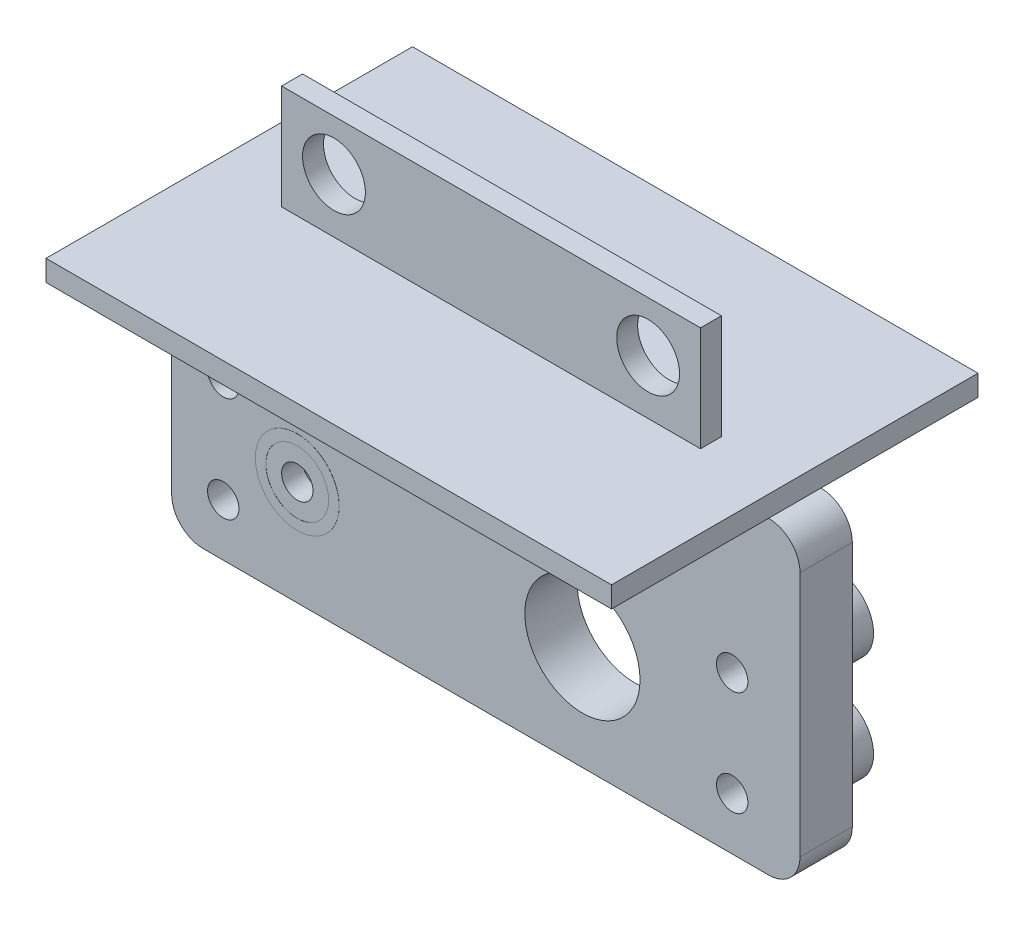
SolidWorks part; units mm, degrees
ref_plane "前视基准面" through (0, 0, 0) normal (0, 0, 1) x (1, 0, 0)
ref_plane "上视基准面" through (0, 0, 0) normal (0, 1, 0) x (1, 0, 0)
ref_plane "右视基准面" through (0, 0, 0) normal (1, 0, 0) x (0, 0, -1)
other "Configuration Table"
sketch "草图1" plane through (0, 0, 0) normal (0, 0, 1) x (1, 0, 0)
  line L0 (0, 0) -> (1.5, 0) construction
  line L2 (-15.5, 19.5) -> (38.5, 19.5)
  line L3 (-18.5, 16.5) -> (-18.5, -7)
  line L4 (-15.5, -10) -> (-9.175, -10)
  line L5 (41.5, 16.5) -> (41.5, -7)
  line L29 (33.3, -10) -> (38.5, -10)
  line L30 (11.5, 18.5) -> (11.5, 10.6886) construction
  line L33 (26.375, 18.5) -> (2.3684, 18.5) construction
  line L34 (33.3, -10) -> (30.825, -10)
  line L35 (-9.175, -10) -> (30.825, -10)
  circle A16 centre (-13.575, 5) radius 1.5
  circle A17 centre (-13.575, -5) radius 1.5
  circle A18 centre (35.025, 5) radius 1.5
  circle A19 centre (35.025, -5) radius 1.5
  arc A20 (38.5, 19.5) -> (41.5, 16.5) centre (38.5, 16.5) cw
  arc A21 (38.5, -10) -> (41.5, -7) centre (38.5, -7) ccw
  arc A22 (-18.5, -7) -> (-15.5, -10) centre (-15.5, -7) ccw
  arc A23 (-15.5, 19.5) -> (-18.5, 16.5) centre (-15.5, 16.5) ccw
  circle A32 centre (20.725, 0) radius 5.5
  dimension "D2" = 3
  dimension "D3" = 3
  dimension "D4" = 60
  dimension "D6" = 3
  dimension "D8" = 14.3
  dimension "D9" = 14.3
  dimension "D10" = 11
  dimension "D11" = 14.875
  dimension "D5" = 3
  dimension "D13" = 3
  dimension "D15" = 10
  dimension "D17" = 34.3
  dimension "D7" = 29.5
  dimension "D16" = 34.3
  dimension "D20" = 10
extrude "凸台-拉伸1" add sketch "草图1" along normal blind 5
sketch "草图3" plane through (0, 0, 5) normal (0, 0, 1) x (1, 0, 0)
  line L0 (-18.5, 16.5) -> (-18.5, -7) construction
  circle A1 centre (-6.5, 0) radius 3
  dimension "D1" = 12
extrude "拉伸-薄壁1" add sketch "草图3" along normal blind 0.01 thin
sketch "草图7" plane through (0, 19.5, 0) normal (0, 1, 0) x (1, 0, 0)
  line L0 (-15.5, -20) -> (-15.5, 15)
  line L1 (-15.5, -5) -> (-15.5, 0) construction
  line L2 (38.5, -20) -> (38.5, 15)
  line L3 (38.5, -5) -> (38.5, 0) construction
  line L4 (38.5, 15) -> (-15.5, 15)
  line L5 (-15.5, -2.5) -> (38.5, -2.5) construction
  line L6 (38.5, -20) -> (-15.5, -20)
  dimension "D1" = 35
extrude "凸台-拉伸2" add sketch "草图7" along normal blind 2
sketch "草图8" plane through (0, 0, 0) normal (0, 0, -1) x (-1, 0, 0)
  circle A0 centre (-35.025, 5) radius 1.5 construction
  circle A1 centre (-35.025, 5) radius 1.5
  circle A2 centre (-35.025, -5) radius 1.5 construction
  circle A3 centre (-35.025, -5) radius 1.5
  circle A4 centre (13.575, 5) radius 1.5 construction
  circle A5 centre (13.575, 5) radius 1.5
  circle A6 centre (13.575, -5) radius 1.5 construction
  circle A7 centre (13.575, -5) radius 1.5
extrude "拉伸-薄壁2" add sketch "草图8" along normal blind 5 thin
ref_plane "基准面1" through (0, 0, 2.5) normal (0, 0, 1) x (1, 0, 0)
sketch "草图10" plane through (0, 0, 2.5) normal (0, 0, 1) x (1, 0, 0)
  line L0 (11.5, 21.5) -> (11.5, -10) construction
  line L1 (-15.5, 21.5) -> (38.5, 21.5) construction
  line L2 (-15.5, -10) -> (38.5, -10) construction
  line L4 (31.5, 21.5) -> (-8.5, 21.5)
  line L5 (-8.5, 21.5) -> (-8.5, 31.5)
  line L7 (11.5, 21.5) -> (11.5, 31.5) construction
  line L8 (31.5, 31.5) -> (-8.5, 31.5)
  line L9 (31.5, 21.5) -> (31.5, 31.5)
  circle A0 centre (26.5, 26.7) radius 3
  circle A1 centre (-3.5, 26.7) radius 3
  point P15 (23.8551, 45.0845)
  dimension "D3" = 6
  dimension "D1" = 40
  dimension "D2" = 10
  dimension "D4" = 5.2
  dimension "D5" = 15
extrude "凸台-拉伸3" add sketch "草图10" along normal blind 2
sketch "草图11" plane through (0, 0, 5) normal (0, 0, 1) x (1, 0, 0)
  circle A0 centre (-6.5, 0) radius 1.5
extrude "切除-拉伸1" cut sketch "草图11" against normal blind 10
sketch "草图12" plane through (0, 0, 0) normal (0, 0, -1) x (-1, 0, 0)
  circle A0 centre (6.5, 0) radius 2.75
  dimension "D1" = 5.5
extrude "切除-拉伸2" cut sketch "草图12" against normal blind 3
